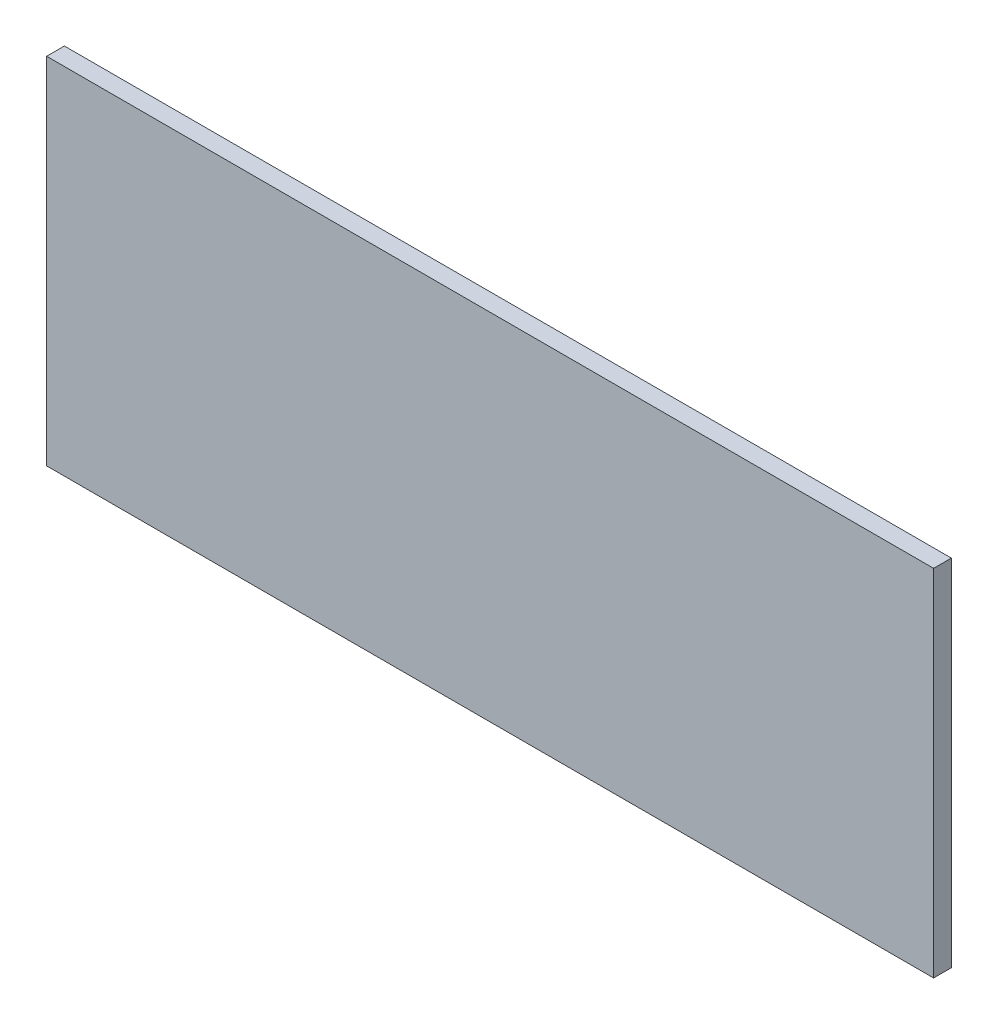
SolidWorks part; units mm, degrees
ref_plane "Front Plane" through (0, 0, 0) normal (0, 0, 1) x (1, 0, 0)
ref_plane "Top Plane" through (0, 0, 0) normal (0, 1, 0) x (1, 0, 0)
ref_plane "Right Plane" through (0, 0, 0) normal (1, 0, 0) x (0, 0, -1)
sketch "Sketch1" plane through (0, 0, 0) normal (0, 0, 1) x (1, 0, 0)
  line L1 (-125, 50) -> (125, 50)
  line L2 (-125, 50) -> (-125, -50)
  line L3 (-125, -50) -> (125, -50)
  line L4 (125, 50) -> (125, -50)
  dimension "D1" = 250
  dimension "D2" = 100
  dimension "D3" = 50
  dimension "D4" = 125
extrude "Boss-Extrude1" add sketch "Sketch1" along normal blind 5
